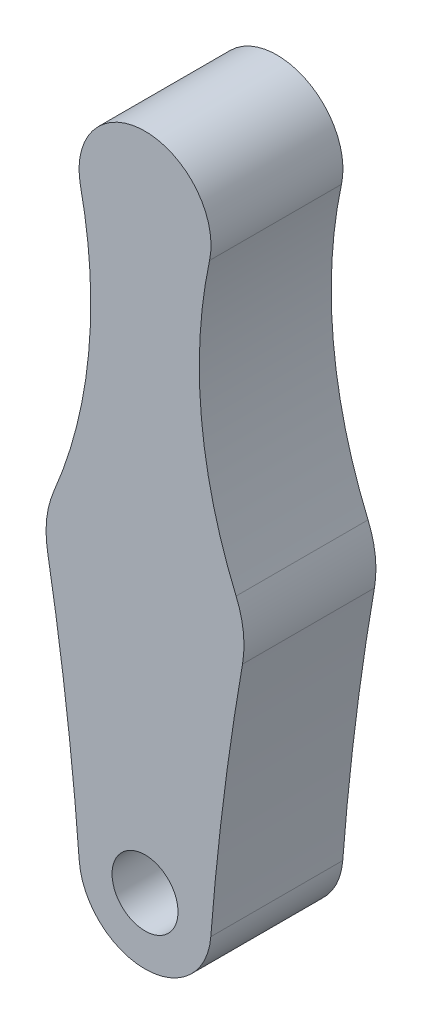
SolidWorks part; units mm, degrees
ref_plane "前视基准面" through (0, 0, 0) normal (0, 0, 1) x (1, 0, 0)
ref_plane "上视基准面" through (0, 0, 0) normal (0, 1, 0) x (1, 0, 0)
ref_plane "右视基准面" through (0, 0, 0) normal (1, 0, 0) x (0, 0, -1)
other "Configuration Table"
sketch "Sketch1" plane through (0, 0, 0) normal (0, 0, 1) x (1, 0, 0)
  line L0 (0, 0) -> (0, 20) construction
  line L1 (0, 20) -> (0, 45) construction
  circle A0 centre (0, 0) radius 5
  circle A1 centre (0, 20) radius 7.5
  arc A2 (-4.9852, -0.3849) -> (-7.3877, 18.7067) centre (-204.3917, -15.7812) ccw
  arc A3 (4.9852, -0.3849) -> (7.3877, 18.7067) centre (204.3917, -15.7812) cw
  circle A5 centre (0, 45) radius 5
  arc A6 (-4.8892, 43.9531) -> (-6.9024, 22.9338) centre (-39.1134, 36.625) cw
  arc A7 (4.8892, 43.9531) -> (6.9024, 22.9338) centre (39.1134, 36.625) ccw
  dimension "D1" = 15
  dimension "D2" = 10
  dimension "D4" = 200
  dimension "D5" = 10
  dimension "D7" = 35
  dimension "D3" = 20
  dimension "D6" = 25
extrude "Boss-Extrude1" add sketch "Sketch1" along normal mid plane 10 contours A7 A5 A6 A1 | A5 | A1 | A0 A3 A1 A2 | A0 A5
sketch "Sketch2" plane through (0, 0, -5) normal (0, 0, -1) x (-1, 0, 0)
  circle A0 centre (0, 0) radius 2.5
  dimension "D1" = 5
extrude "Cut-Extrude1" cut sketch "Sketch2" against normal blind 10
